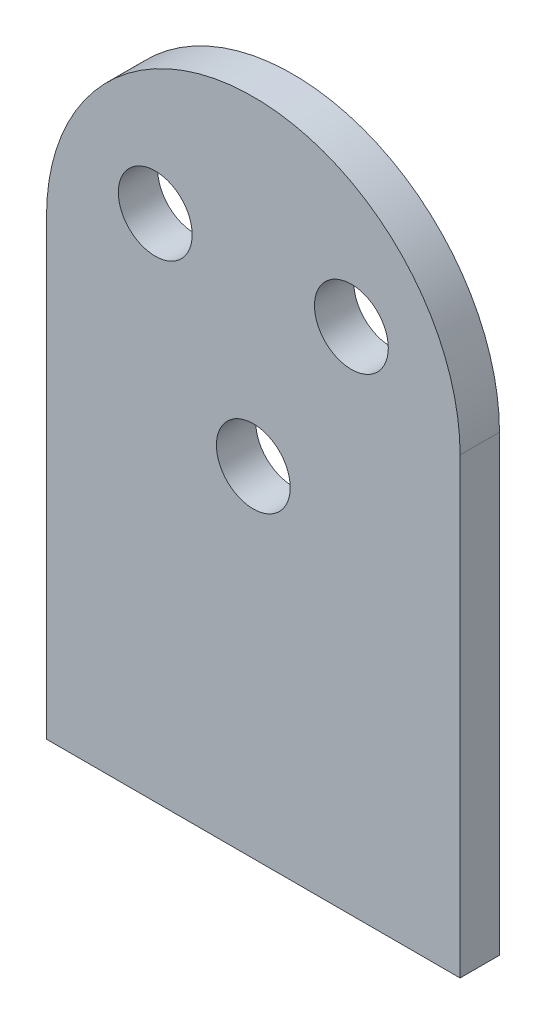
SolidWorks part; units mm, degrees
ref_plane "Front Plane" through (0, 0, 0) normal (0, 0, 1) x (1, 0, 0)
ref_plane "Top Plane" through (0, 0, 0) normal (0, 1, 0) x (1, 0, 0)
ref_plane "Right Plane" through (0, 0, 0) normal (1, 0, 0) x (0, 0, -1)
sketch "Sketch1" plane through (0, 0, 0) normal (0, 0, 1) x (1, 0, 0)
  line L0 (-4.2, 0) -> (-4.2, -9.2)
  line L1 (-4.2, -9.2) -> (4.2, -9.2)
  line L2 (4.2, -9.2) -> (4.2, 0)
  line L3 (-4.4, 0) -> (-4.4, -9.4)
  line L4 (-4.4, -9.4) -> (4.4, -9.4)
  line L5 (4.4, -9.4) -> (4.4, 0)
  line L6 (-4.4, 0) -> (-4.4, -9.4) construction
  line L7 (-4.4, -9.4) -> (4.4, -9.4) construction
  line L8 (4.4, -9.4) -> (4.4, 0) construction
  arc A0 (4.2, 0) -> (-4.2, 0) centre (0, 0) ccw
  arc A1 (4.4, 0) -> (-4.4, 0) centre (0, 0) ccw
  arc A2 (4.4, 0) -> (-4.4, 0) centre (0, 0) ccw construction
  circle A3 centre (0, -2.3) radius 0.75 construction
  circle A4 centre (1.9919, 1.15) radius 0.75 construction
  circle A5 centre (-1.9919, 1.15) radius 0.75 construction
  circle A6 centre (0, -2.3) radius 0.75
  circle A7 centre (1.9919, 1.15) radius 0.75
  circle A8 centre (-1.9919, 1.15) radius 0.75
  dimension "D1" = 0
  dimension "D2" = 0.2
extrude "Boss-Extrude2" add sketch "Sketch1" along normal blind 0.8
